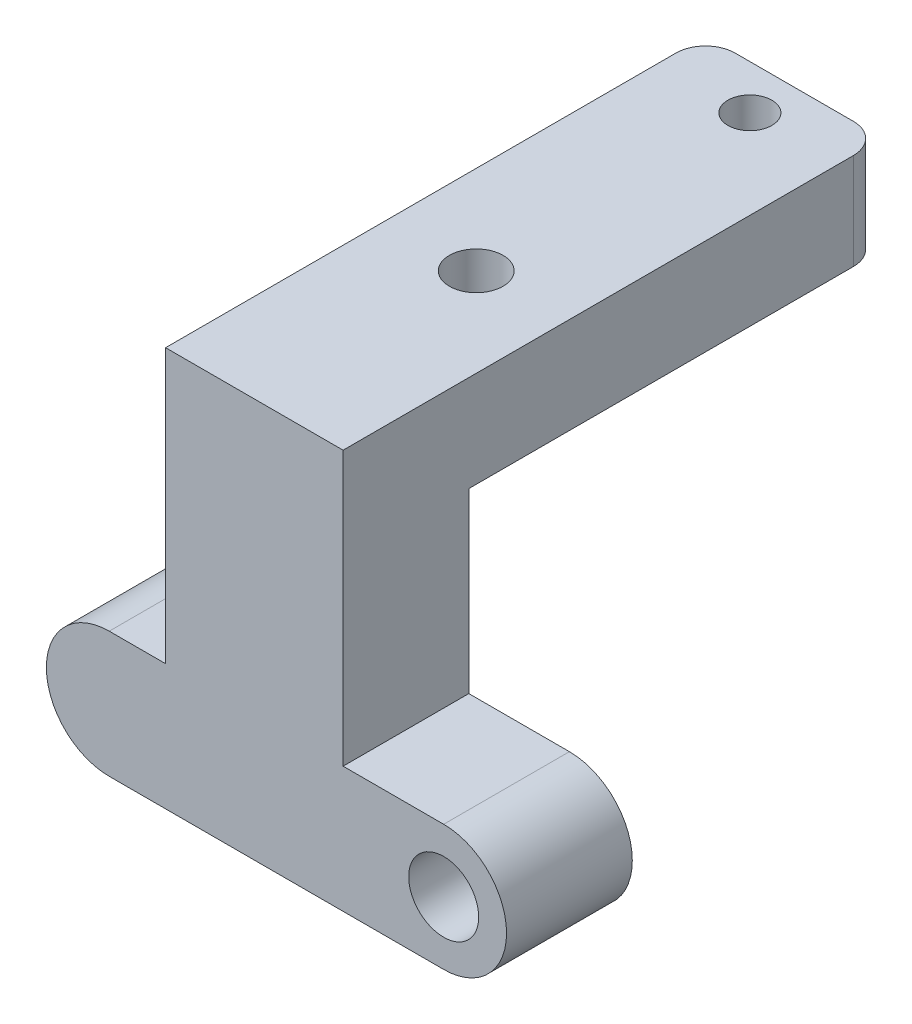
SolidWorks part; units mm, degrees
ref_plane "前基準面" through (0, 0, 0) normal (0, 0, 1) x (1, 0, 0)
ref_plane "上基準面" through (0, 0, 0) normal (0, 1, 0) x (1, 0, 0)
ref_plane "右基準面" through (0, 0, 0) normal (1, 0, 0) x (0, 0, -1)
sketch "草圖1" plane through (0, 0, 0) normal (0, 0, 1) x (1, 0, 0)
  line L0 (10.8322, 0) -> (-11.7761, 0) construction
  line L1 (10.8322, -4.25) -> (-11.7761, -4.25)
  line L2 (10.8322, 4.25) -> (4.0322, 4.25)
  line L3 (4.0322, 4.25) -> (4.0322, 16.25)
  line L6 (-7.9678, 4.25) -> (-11.7761, 4.25)
  line L7 (-7.9678, 4.25) -> (4.0322, 4.25)
  line L8 (-7.9678, 4.25) -> (-7.9678, 16.25)
  line L9 (-7.9678, 16.25) -> (4.0322, 16.25)
  arc A0 (10.8322, -4.25) -> (10.8322, 4.25) centre (10.8322, 0) ccw
  arc A1 (-11.7761, 4.25) -> (-11.7761, -4.25) centre (-11.7761, 0) ccw
  circle A2 centre (10.8322, 0) radius 2.366
  point P3 (-0.472, 0)
  dimension "D1" = 8.5
  dimension "D2" = 12
  dimension "D3" = 6.8
  dimension "D4" = 12
extrude "填料-伸長1" add sketch "草圖1" against normal blind 8.5
sketch "草圖3" plane through (0, 0, 0) normal (0, 0, 1) x (1, 0, 0)
  line L0 (-7.9678, 16.25) -> (4.0322, 16.25)
  line L1 (-7.9678, 16.25) -> (-7.9678, 22.75)
  line L2 (4.0322, 16.25) -> (4.0322, 22.75)
  line L3 (-7.9678, 22.75) -> (4.0322, 22.75)
  dimension "D1" = 6.5
extrude "填料-伸長3" add sketch "草圖3" against normal blind 36.5
sketch "草圖4" plane through (0, 22.75, 0) normal (0, 1, 0) x (1, 0, 0)
  line L0 (-1.9678, 36.5) -> (-1.9678, 0) construction
  line L1 (4.0322, 36.5) -> (-7.9678, 36.5) construction
  line L2 (4.0322, 0) -> (-7.9678, 0) construction
  circle A0 centre (-1.9678, 33.5) radius 1.4838
  circle A1 centre (-1.9678, 15) radius 1.8139
  dimension "D1" = 18.5
  dimension "D2" = 3
extrude "除料-伸長1" cut sketch "草圖4" against normal through all
fillet "圓角1" radius 2 2 edges at (-7.9678, 19.5, -36.5) (4.0322, 19.5, -36.5)
